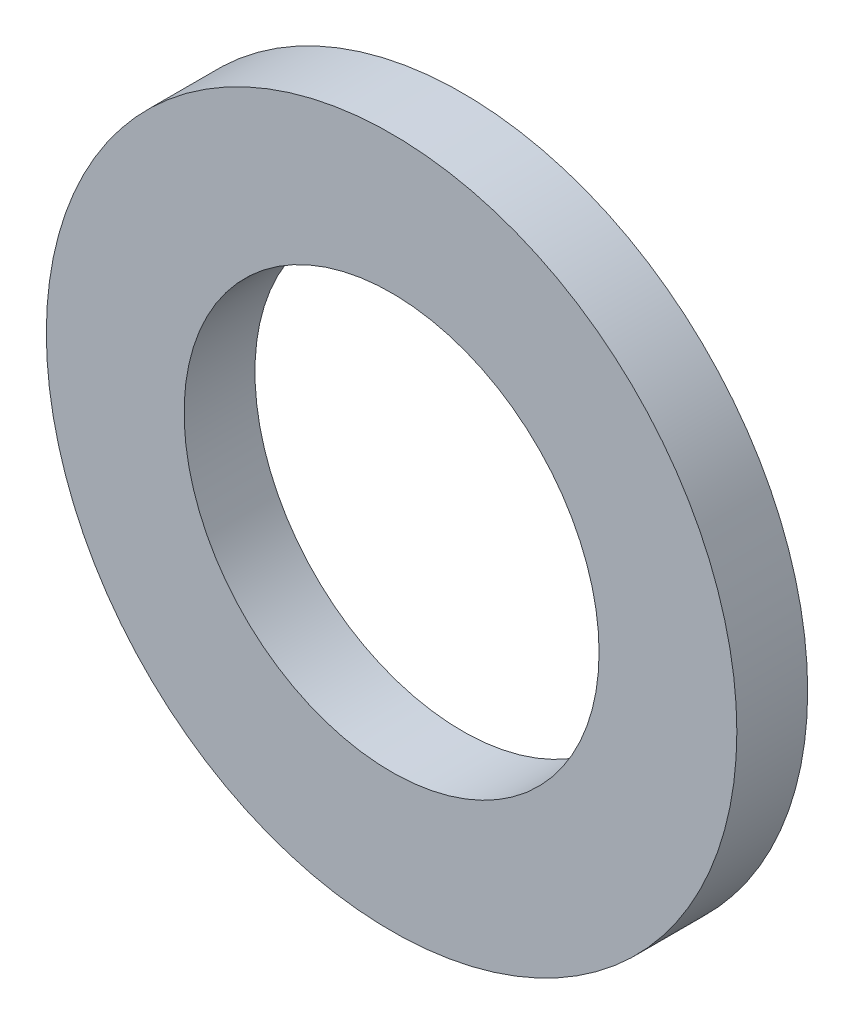
SolidWorks part; units mm, degrees
ref_plane "Front Plane" through (0, 0, 0) normal (0, 0, 1) x (1, 0, 0)
ref_plane "Top Plane" through (0, 0, 0) normal (0, 1, 0) x (1, 0, 0)
ref_plane "Right Plane" through (0, 0, 0) normal (1, 0, 0) x (0, 0, -1)
sketch "Sketch1" plane through (0, 0, 0) normal (0, 0, 1) x (1, 0, 0)
  circle A0 centre (0, 0) radius 2.3813
  circle A1 centre (0, 0) radius 3.9624
  dimension "D1" = 4.7625
  dimension "D2" = 7.9248
extrude "Boss-Extrude1" add sketch "Sketch1" along normal blind 0.8128
